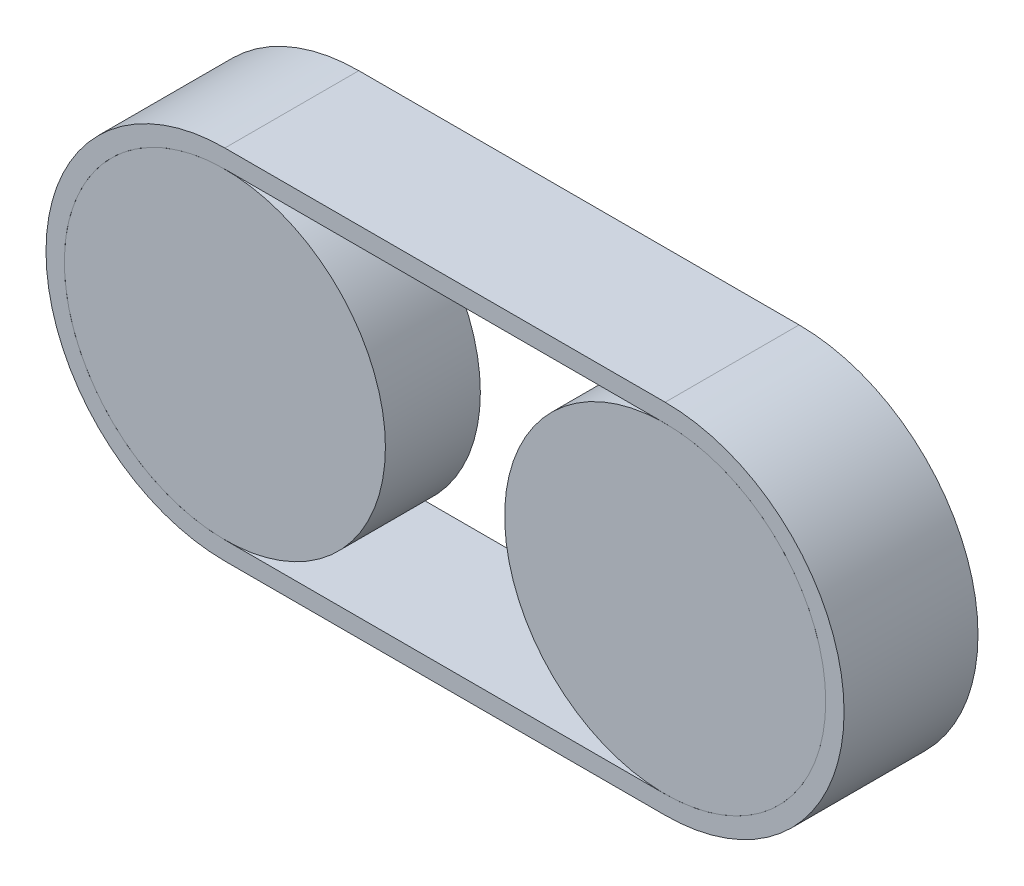
SolidWorks part; units mm, degrees
ref_plane "Front Plane" through (0, 0, 0) normal (0, 0, 1) x (1, 0, 0)
ref_plane "Top Plane" through (0, 0, 0) normal (0, 1, 0) x (1, 0, 0)
ref_plane "Right Plane" through (0, 0, 0) normal (1, 0, 0) x (0, 0, -1)
sketch "Sketch1" plane through (0, 0, 0) normal (0, 0, 1) x (1, 0, 0)
  line L0 (-24, 0) -> (0, 0) construction
  line L1 (0, 0) -> (24, 0) construction
  line L2 (-24, 19.5) -> (24, 19.5)
  line L3 (24, 17.5) -> (-24, 17.5)
  line L4 (-24, -19.5) -> (24, -19.5)
  line L6 (24, -17.5) -> (-24, -17.5)
  arc A0 (-24, 17.5) -> (-24, -17.5) centre (-24, 0) ccw
  arc A1 (24, -17.5) -> (24, 17.5) centre (24, 0) ccw
  arc A2 (-24, 19.5) -> (-24, -19.5) centre (-24, 0) ccw
  arc A3 (24, -19.5) -> (24, 19.5) centre (24, 0) ccw
  circle A4 centre (-24, 0) radius 17.5 construction
  circle A5 centre (-24, 0) radius 19.5 construction
  circle A6 centre (24, 0) radius 19.5 construction
  circle A7 centre (24, 0) radius 17.5 construction
  dimension "D1" = 2
extrude "Boss-Extrude1" add sketch "Sketch1" along normal blind 14.6
sketch "Sketch2" plane through (0, 0, 14.6) normal (0, 0, 1) x (1, 0, 0)
  circle A0 centre (-24, 0) radius 17.5
  circle A1 centre (24, 0) radius 17.5
extrude "Boss-Extrude2" add sketch "Sketch2" against normal blind 10.35 separate body
